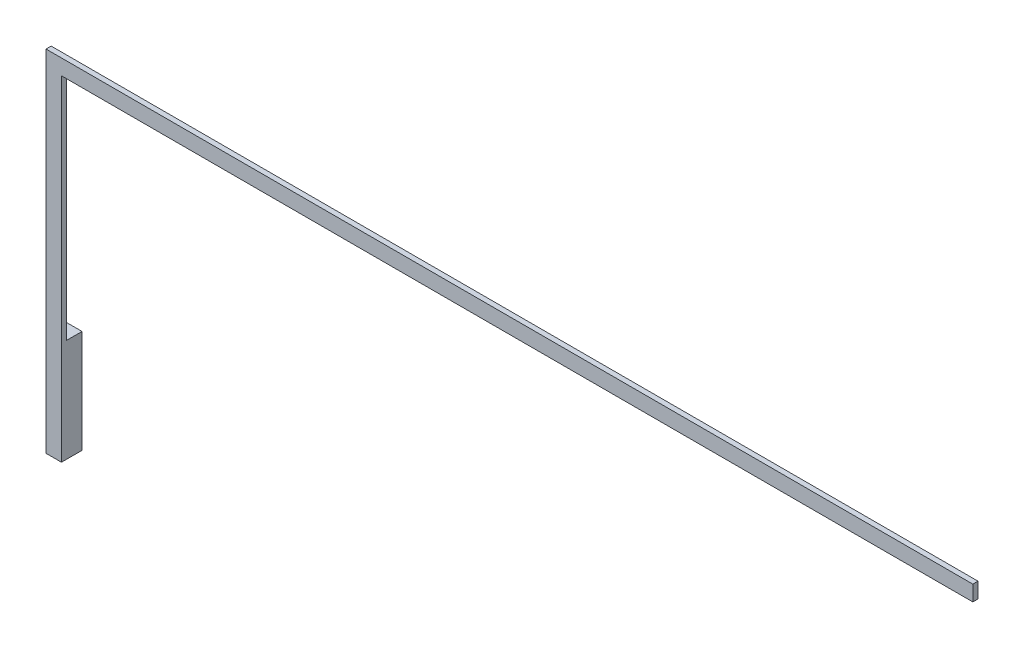
SolidWorks part; units mm, degrees
ref_plane "Front Plane" through (0, 0, 0) normal (0, 0, 1) x (1, 0, 0)
ref_plane "Top Plane" through (0, 0, 0) normal (0, 1, 0) x (1, 0, 0)
ref_plane "Right Plane" through (0, 0, 0) normal (1, 0, 0) x (0, 0, -1)
sketch "Sketch1" plane through (0, 0, 0) normal (0, 0, 1) x (1, 0, 0)
  line L11 (0, 0) -> (0, -340)
  line L12 (0, -340) -> (15, -340)
  line L15 (15, -14.9968) -> (15, -340)
  line L16 (0, 0) -> (900, 0)
  line L17 (900, 0) -> (900, -14.9968)
  line L22 (900, -14.9968) -> (15, -14.9968)
  dimension "D1" = 15
  dimension "D2" = 14.9968
  dimension "D3" = 340
  dimension "D4" = 900
extrude "Boss-Extrude1" add sketch "Sketch1" along normal blind 5
sketch "Sketch3" plane through (0, 0, 0) normal (0, 0, 1) x (1, 0, 0)
  line L0 (0, 0) -> (0, -340) construction
  line L1 (15, -340) -> (0, -340)
  line L2 (15, -340) -> (15, -240)
  line L3 (15, -240) -> (0, -240)
  line L4 (0, -340) -> (0, -240)
  dimension "D1" = 100
extrude "Boss-Extrude2" add sketch "Sketch3" against normal blind 15
